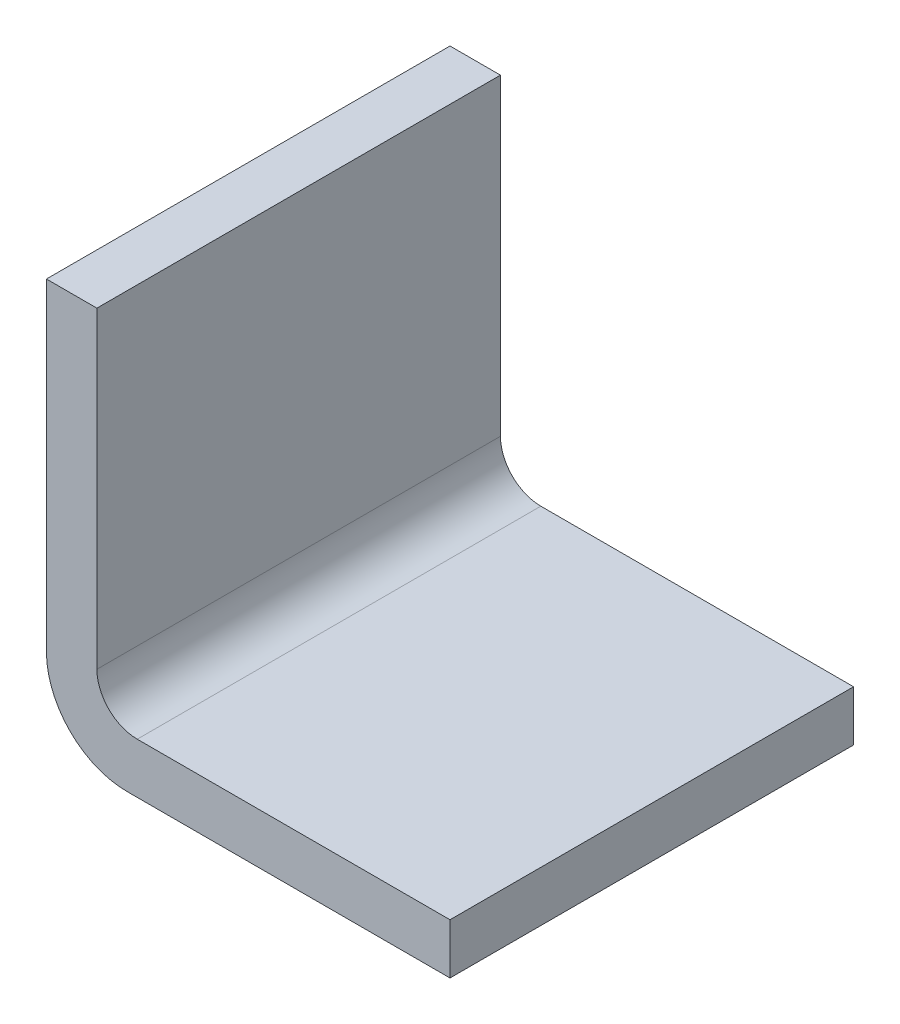
SolidWorks part; units mm, degrees
ref_plane "Front Plane" through (0, 0, 0) normal (0, 0, 1) x (1, 0, 0)
ref_plane "Top Plane" through (0, 0, 0) normal (0, 1, 0) x (1, 0, 0)
ref_plane "Right Plane" through (0, 0, 0) normal (1, 0, 0) x (0, 0, -1)
sketch "Sketch1" plane through (0, 0, 0) normal (0, 0, 1) x (1, 0, 0)
  line L0 (2.54, 0) -> (12.7, 0)
  line L1 (12.7, 0) -> (12.7, 1.5875)
  line L2 (12.7, 1.5875) -> (2.8575, 1.5875)
  line L3 (1.5875, 2.8575) -> (1.5875, 12.7)
  line L4 (1.5875, 12.7) -> (0, 12.7)
  line L5 (0, 12.7) -> (0, 2.54)
  arc A0 (2.8575, 1.5875) -> (1.5875, 2.8575) centre (2.8575, 2.8575) cw
  arc A1 (2.54, 0) -> (0, 2.54) centre (2.54, 2.54) cw
  point P11 (0, 0)
  dimension "D5" = 1.27
  dimension "D6" = 2.54
  dimension "D1" = 12.7
  dimension "D2" = 12.7
  dimension "D3" = 1.5875
  dimension "D4" = 1.5875
extrude "Boss-Extrude1" add sketch "Sketch1" along normal blind 12.7
